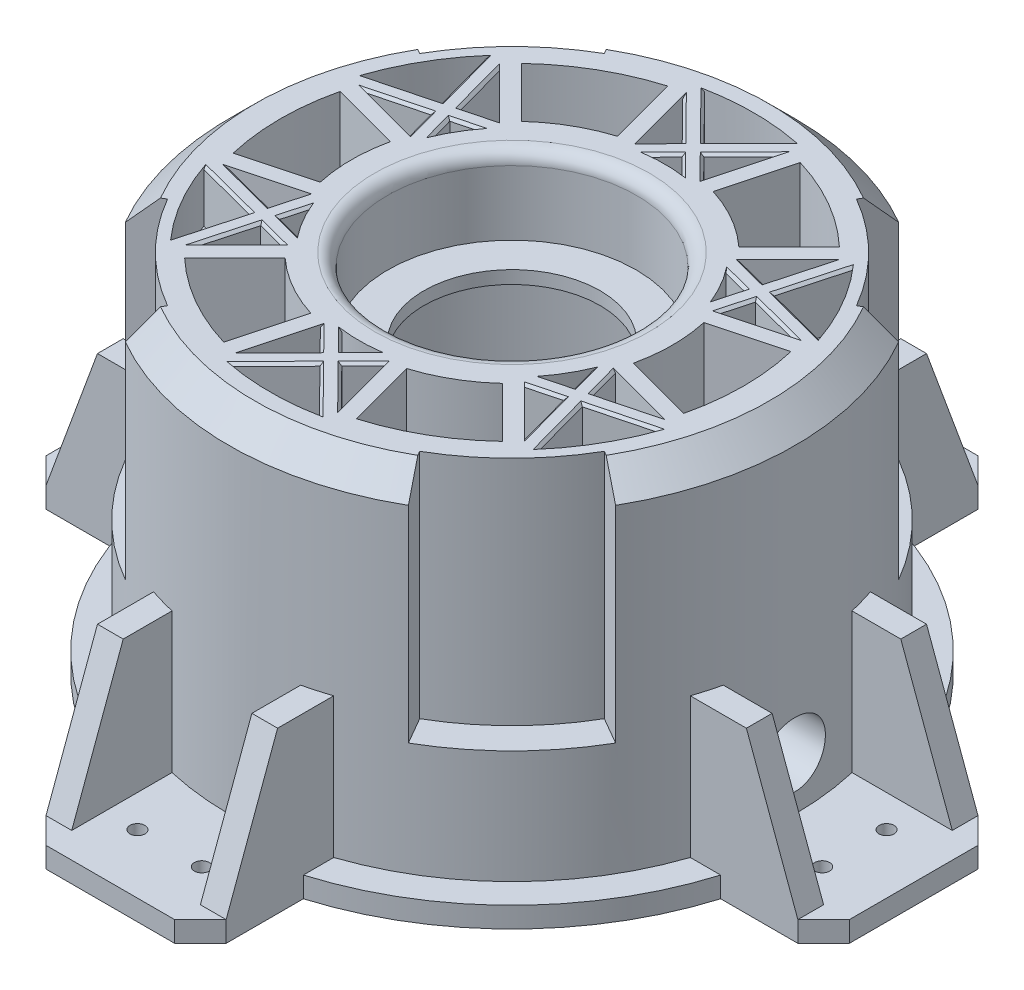
SolidWorks part; units mm, degrees
material "PETG"
ref_plane "Front Plane" through (0, 0, 0) normal (0, 0, 1) x (1, 0, 0)
ref_plane "Top Plane" through (0, 0, 0) normal (0, 1, 0) x (1, 0, 0)
ref_plane "Right Plane" through (0, 0, 0) normal (1, 0, 0) x (0, 0, -1)
sketch "Sketch1" plane through (0, 0, 0) normal (0, 1, 0) x (1, 0, 0)
  circle A0 centre (0, 0) radius 45
  circle A1 centre (0, 0) radius 60.625
  dimension "D1" = 90
  dimension "D2" = 121.25
extrude "Boss-Extrude1" add sketch "Sketch1" along normal blind 4
sketch "Sketch2" plane through (0, 4, 0) normal (0, 1, 0) x (1, 0, 0)
  circle A0 centre (0, 0) radius 45
  circle A1 centre (0, 0) radius 55
  dimension "D1" = 90
  dimension "D2" = 110
extrude "Boss-Extrude2" add sketch "Sketch2" along normal blind 67
sketch "Sketch3" plane through (0, 0, 0) normal (0, 0, 1) x (1, 0, 0)
  line L0 (-60.625, 0) -> (60.625, 0) construction
  line L1 (11.25, 0) -> (19.25, 0)
  line L2 (11.25, 0) -> (11.25, 30.5)
  line L3 (11.25, 30.5) -> (19.25, 30.5)
  line L4 (19.25, 0) -> (19.25, 30.5)
  line L6 (-46.75, 30.5) -> (-31.75, 30.5)
  line L7 (-46.75, 30.5) -> (-46.75, 22.5)
  line L8 (-46.75, 22.5) -> (-31.75, 22.5)
  line L9 (-31.75, 30.5) -> (-31.75, 22.5)
  dimension "D1" = 8
  dimension "D2" = 11.25
  dimension "D3" = 30.5
  dimension "D4" = 43
  dimension "D5" = 15
  dimension "D6" = 22.5
extrude "Boss-Extrude3" add sketch "Sketch3" along normal mid plane 26
sketch "Sketch4" plane through (11.25, 0, 0) normal (-1, 0, 0) x (0, 0, 1)
  line L0 (0, 0) -> (0, 71) construction
  line L1 (55, 71) -> (-55, 71) construction
  line L3 (-5, 21) -> (5, 21)
  line L4 (-5, 21) -> (-5, 5)
  line L5 (-5, 5) -> (5, 5)
  line L6 (5, 21) -> (5, 5)
  line L7 (-5, 21) -> (5, 5) construction
  line L8 (-5, 5) -> (5, 21) construction
  point P5 (0, 13)
  dimension "D1" = 10
  dimension "D2" = 5
  dimension "D3" = 16
extrude "Cut-Extrude1" cut sketch "Sketch4" against normal up to next (8 mm away)
sketch "Sketch5" plane through (11.25, 0, 0) normal (-1, 0, 0) x (0, 0, 1)
  line L0 (0, 0) -> (0, 71) construction
  line L1 (55, 71) -> (-55, 71) construction
  circle A0 centre (0, 14) radius 6.25
  dimension "D1" = 12.5
  dimension "D2" = 14
extrude "Cut-Extrude2" cut sketch "Sketch5" against normal through all
sketch "Sketch6" plane through (0, 30.5, 0) normal (0, 1, 0) x (1, 0, 0)
  line L0 (-45, 0) -> (45, 0) construction
  line L1 (-31.75, -13) -> (-31.75, 13) construction
  line L2 (-34.25, 5) -> (13.75, 5) construction
  line L3 (-34.25, 5) -> (-34.25, -5) construction
  line L4 (-34.25, -5) -> (13.75, -5) construction
  line L5 (13.75, 5) -> (13.75, -5) construction
  line L6 (11.25, -13) -> (11.25, 13) construction
  circle A0 centre (0, 0) radius 45 construction
  arc A1 (-43.0813, 13) -> (-43.0813, -13) centre (0, 0) ccw construction
  circle A2 centre (-34.25, 5) radius 1.3
  circle A3 centre (-34.25, -5) radius 1.3
  circle A4 centre (13.75, 5) radius 1.3
  circle A5 centre (13.75, -5) radius 1.3
  dimension "D5" = 2.6
  dimension "D1" = 5
  dimension "D2" = 5
  dimension "D3" = 2.5
  dimension "D4" = 2.5
extrude "Cut-Extrude3" cut sketch "Sketch6" against normal blind 7.2
sketch "Sketch7" plane through (0, 0, 0) normal (0, -1, 0) x (1, 0, 0)
  line L0 (11.25, 13) -> (25.2498, 37.2484)
  line L1 (19.25, 0) -> (71.19, 0) construction
  line L2 (19.25, 13) -> (19.25, -13) construction
  line L3 (11.25, -13) -> (25.2498, -37.2484)
  line L4 (11.25, 13) -> (11.25, -13)
  line L5 (24.25, 19.5167) -> (27.3618, 24.9065)
  line L7 (24.25, -19.5167) -> (27.3618, -24.9065)
  line L8 (24.25, 19.5167) -> (24.25, -19.5167)
  line L9 (19.25, 10.8564) -> (19.25, -10.8564) construction
  line L10 (19.25, 10.8564) -> (27.3618, 24.9065) construction
  line L11 (19.25, -10.8564) -> (27.3618, -24.9065) construction
  circle A0 centre (0, 0) radius 45 construction
  arc A1 (25.2498, -37.2484) -> (25.2498, 37.2484) centre (0, 0) ccw
  arc A2 (27.3618, -24.9065) -> (27.3618, 24.9065) centre (0, 0) ccw
  dimension "D1" = 60
  dimension "D3" = 5
  dimension "D2" = 8
extrude "Boss-Extrude4" add sketch "Sketch7" against normal blind 4
sketch "Sketch9" plane through (0, 0, 0) normal (0, -1, 0) x (1, 0, 0)
  line L0 (0, 0) -> (-78.0443, 0) construction
  line L1 (-78.0443, 17.5) -> (-78.0443, -17.5)
  line L2 (-78.0443, 17.5) -> (-58.0443, 17.5)
  line L3 (-78.0443, -17.5) -> (-58.0443, -17.5)
  circle A0 centre (0, 0) radius 60.625 construction
  arc A2 (-58.0443, 17.5) -> (-58.0443, -17.5) centre (0, 0) ccw
  point P6 (-78.0443, 0)
  dimension "D1" = 35
  dimension "D2" = 20
extrude "Boss-Extrude5" add sketch "Sketch9" against normal up to surface (4 mm away) up to face at (0, 4, 55)
chamfer "Chamfer1" distance 5 angle 45 2 edges at (-78.0443, 2, -17.5) (-78.0443, 2, 17.5)
sketch "Sketch10" plane through (0, 0, 17.5) normal (0, 0, 1) x (1, 0, 0)
  line L0 (-43.2881, 0) -> (-43.2881, 31.2079)
  line L3 (-43.2881, 31.2079) -> (-63.0443, 31.2079)
  line L4 (-63.0443, 31.2079) -> (-73.0443, 4)
  line L5 (-73.0443, 4) -> (-73.0443, 0)
  line L6 (-73.0443, 0) -> (-43.2881, 0)
  dimension "D1" = 10
extrude "Boss-Extrude6" add sketch "Sketch10" against normal blind 5
sketch "Sketch11" plane through (0, 4, 0) normal (0, 1, 0) x (1, 0, 0)
  line L0 (-55, 0) -> (-78.0443, 0) construction
  line L1 (-78.0443, -12.5) -> (-78.0443, 12.5) construction
  line L2 (-66.5221, 0) -> (-66.5221, -12.5) construction
  line L3 (-63.0443, -12.5) -> (-73.0443, -12.5) construction
  circle A1 centre (-66.5221, -6.25) radius 1.45
  circle A2 centre (0, 0) radius 55 construction
  arc A3 (-52.1416, -17.5) -> (-53.5607, -12.5) centre (0, 0) ccw construction
  dimension "D1" = 2.9
extrude "Cut-Extrude5" cut sketch "Sketch11" against normal blind 5
mirror "Mirror1" about plane through (0, 0, 0) normal (0, 0, 1) of "Cut-Extrude5", "Boss-Extrude6"
pattern_circular "CirPattern1" count 4 over 360 about axis through (0, 0, 0) along (0, 1, 0) of "Mirror1", "Boss-Extrude5", "Chamfer1", "Boss-Extrude6", "Cut-Extrude5"
sketch "Sketch12" plane through (0, 71, 0) normal (0, 1, 0) x (1, 0, 0)
  line L0 (-49, 0) -> (49, 0) construction
  line L1 (0, 49) -> (0, -49) construction
  line L2 (-42.4352, -24.5) -> (-47.6314, -27.5)
  line L3 (-24.5, -42.4352) -> (-27.5, -47.6314)
  arc A1 (-42.4352, -24.5) -> (-24.5, -42.4352) centre (0, 0) ccw
  arc A3 (-47.6314, -27.5) -> (-27.5, -47.6314) centre (0, 0) ccw
  arc A4 (-52.1416, -17.5) -> (-17.5, -52.1416) centre (0, 0) ccw construction
  circle A5 centre (0, 0) radius 55 construction
  dimension "D1" = 30
  dimension "D2" = 30
extrude "Cut-Extrude6" cut sketch "Sketch12" against normal blind 45
pattern_circular "CirPattern2" count 4 over 360 about axis through (0, 71, 0) along (0, -1, 0) of "Cut-Extrude6"
sketch "Sketch13" plane through (0, 71, 0) normal (0, 1, 0) x (1, 0, 0)
  line L0 (-7.5, 23.0085) -> (-12.8876, 43.1151)
  line L1 (0, 0) -> (-24.2, 0) construction
  line L2 (0, 24.2) -> (0, 45) construction
  line L3 (7.5, 23.0085) -> (12.8876, 43.1151)
  line L4 (16.1759, 17.9994) -> (30.895, 32.7185)
  line L5 (23.6759, 5.009) -> (43.7825, 10.3966)
  line L6 (23.6759, -5.009) -> (43.7825, -10.3966)
  line L7 (16.1759, -17.9994) -> (30.895, -32.7185)
  line L8 (7.5, -23.0085) -> (12.8876, -43.1151)
  line L9 (-7.5, -23.0085) -> (-12.8876, -43.1151)
  line L10 (-16.1759, -17.9994) -> (-30.895, -32.7185)
  line L11 (-23.6759, -5.009) -> (-43.7825, -10.3966)
  line L12 (-23.6759, 5.009) -> (-43.7825, 10.3966)
  line L13 (-16.1759, 17.9994) -> (-30.895, 32.7185)
  circle A0 centre (0, 0) radius 45
  circle A1 centre (0, 0) radius 24.2
  circle A2 centre (0, 0) radius 24.2
  circle A3 centre (0, 0) radius 45
  circle A4 centre (0, 0) radius 24.2
  circle A5 centre (0, 0) radius 45
  circle A6 centre (0, 0) radius 24.2
  circle A7 centre (0, 0) radius 45
  circle A8 centre (0, 0) radius 24.2
  circle A9 centre (0, 0) radius 45
  circle A10 centre (0, 0) radius 24.2
  circle A11 centre (0, 0) radius 45
  circle A12 centre (0, 0) radius 31.2
  point P45 (0, 0)
  circle M17 centre (0, 0) radius 45
  dimension "D2" = 90
  dimension "D4" = 7.5
  dimension "D3" = 75
  dimension "D1" = 20.8
  dimension "D6" = 7
  dimension "D5" = 6
extrude "Boss-Extrude7" add sketch "Sketch13" against normal blind 17.5 contours A1 L3 L0 M17 | A1 L13 L12 M17 | A1 L11 L10 M17 | A1 L9 L8 M17 | A1 L7 L6 M17 | A1 L5 L4 M17 | L13 A12 L12 A1 | L12 A12 L11 A1 | L11 A12 L10 A1 | L0 A12 L13 A1 | L3 A12 L0 A1 | L4 A12 L3 A1 | L5 A12 L4 A1 | L6 A12 L5 A1 | L7 A12 L6 A1 | L8 A12 L7 A1 | L9 A12 L8 A1 | L10 A12 L9 A1
sketch "Sketch14" plane through (0, 53.5, 0) normal (0, -1, 0) x (1, 0, 0)
  circle A0 centre (0, 0) radius 24.125
  circle A1 centre (0, 0) radius 17.125
  dimension "D1" = 48.25
  dimension "D2" = 7
extrude "Boss-Extrude8" add sketch "Sketch14" against normal blind 2.5
fillet "Fillet1" radius 2.5 1 edges at (0, 71, 24.2)
chamfer "Chamfer2" distance 5 angle 45 4 edges at (0, 71, -55) (55, 71, 0) (-55, 71, 0) (0, 71, 55)
sketch "Sketch16" plane through (0, 71, 0) normal (0, 1, 0) x (1, 0, 0)
  line L0 (9.3137, 29.7774) -> (12.8876, 43.1151) construction
  line L1 (-9.3137, 29.7774) -> (-12.8876, 43.1151) construction
  line L2 (9.3137, 29.7774) -> (12.8876, 43.1151)
  line L3 (-9.3137, 29.7774) -> (-12.8876, 43.1151)
  line L4 (9.9898, 43.8915) -> (10.5041, 45.8112)
  line L5 (-9.9898, 43.8915) -> (-10.5041, 45.8112)
  line L6 (-9.3137, 29.7774) -> (-8.1479, 25.4264)
  line L7 (9.3137, 29.7774) -> (8.1479, 25.4264)
  line L8 (-12.8876, 43.1151) -> (-14.1821, 47.9465)
  line L9 (12.8577, 43.1102) -> (12.8876, 43.1151)
  line L10 (12.8876, 43.1151) -> (14.1821, 47.9465)
  line L11 (-6.416, 30.5539) -> (-9.9898, 43.8915)
  line L12 (-6.416, 30.5539) -> (-6.0219, 29.0831)
  line L13 (6.416, 30.5539) -> (6.0219, 29.0831)
  line L14 (6.416, 30.5539) -> (9.9898, 43.8915)
  line L15 (12.3726, 46.0707) -> (12.4025, 46.0756)
  line L16 (-10.5041, 45.8112) -> (6.0219, 29.0831)
  line L17 (-6.0219, 29.0831) -> (10.5041, 45.8112)
  line L18 (-3.5094, 29.4919) -> (9.7194, 42.8825)
  line L19 (-9.7194, 42.8825) -> (4.9548, 28.0289)
  line L20 (-6.4717, 30.7621) -> (8.757, 46.177)
  line L21 (-8.757, 46.177) -> (7.0889, 30.1373)
  line L22 (-11.5712, 44.757) -> (4.9548, 28.0289) construction
  line L23 (-9.437, 46.8654) -> (7.0889, 30.1373) construction
  line L24 (-4.9548, 28.0289) -> (11.5712, 44.757) construction
  line L25 (-7.0889, 30.1373) -> (9.437, 46.8654) construction
  circle A0 centre (0, 0) radius 26.7 construction
  arc A1 (8.1479, 25.4264) -> (-8.1479, 25.4264) centre (0, 0) ccw
  arc A2 (14.1821, 47.9465) -> (-14.1821, 47.9465) centre (0, 0) ccw
  arc A3 (10.5041, 45.8112) -> (-10.5041, 45.8112) centre (0, 0) ccw
  arc A4 (25, 43.3013) -> (-25, 43.3013) centre (0, 0) ccw construction
  arc A5 (6.0219, 29.0831) -> (-6.0219, 29.0831) centre (0, 0) ccw
  point P37 (-9.7466, 42.9052)
  point P39 (-8.7909, 46.1705)
  point P41 (10.0093, 43.1092)
  point P44 (8.7627, 46.1759)
  point P47 (7.0911, 30.059)
  point P48 (-6.4679, 30.6688)
  point P49 (-3.4676, 29.4214)
  point P50 (7.0911, 30.059)
  point P51 (9.7372, 42.87)
  point P52 (7.0911, 30.059)
  dimension "D1" = 3
  dimension "D2" = 1.5
  dimension "D3" = 1.5
extrude "Cut-Extrude7" cut sketch "Sketch16" against normal blind 10 contours A5 L13 L14 L4 A3 L5 L11 L12 | A5 L19 L18 | L18 L21 L14 | L11 L20 L19
chamfer "Chamfer3" distance 0.5 angle 45 8 edges at (-1.7547, 71, -31.2681) (1.7547, 71, -31.2681) (4.2901, 71, -32.9703) (5.914, 71, -39.0306) (4.3785, 71, -41.745) (-4.3785, 71, -41.745) (-4.2901, 71, -32.9703) (-5.914, 71, -39.0306)
pattern_circular "CirPattern4" count 6 over 360 about axis through (0, 0, 0) along (0, 1, 0) of "Cut-Extrude7", "Chamfer3"
fillet "Fillet2" radius 2.5 7 edges at (-45, 22.5, 0) (0, 53.5, -45) (38.9711, 53.5, -22.5) (38.9711, 53.5, 22.5) (0, 53.5, 45) (-38.9711, 53.5, -22.5) (-38.9711, 53.5, 22.5)
